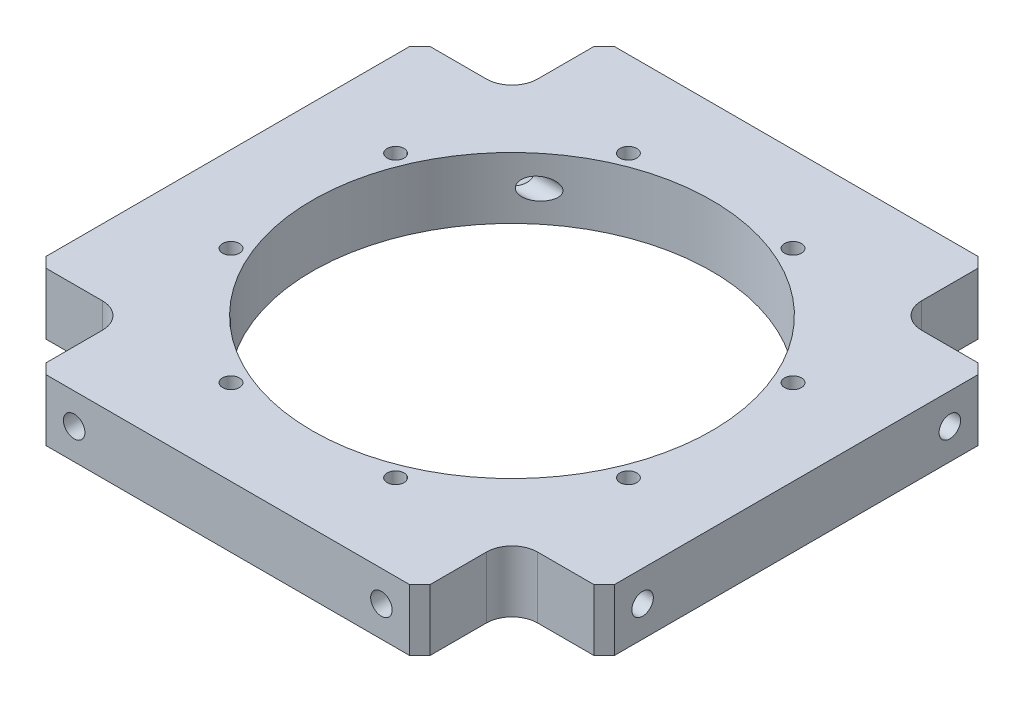
SolidWorks part; units mm, degrees
material "6061-T6 (SS)"
ref_plane "前视基准面" through (0, 0, 0) normal (0, 0, 1) x (1, 0, 0)
ref_plane "上视基准面" through (0, 0, 0) normal (0, 1, 0) x (1, 0, 0)
ref_plane "右视基准面" through (0, 0, 0) normal (1, 0, 0) x (0, 0, -1)
sketch "草图1" plane through (0, 0, 0) normal (0, 1, 0) x (1, 0, 0)
  line L1 (55.5, -55.5) -> (-55.5, -55.5)
  line L2 (55.5, -55.5) -> (55.5, 55.5)
  line L3 (55.5, 55.5) -> (-55.5, 55.5)
  line L4 (-55.5, -55.5) -> (-55.5, 55.5)
  line L5 (55.5, -55.5) -> (-55.5, 55.5) construction
  line L6 (55.5, 55.5) -> (-55.5, -55.5) construction
  point P0 (0, 0)
  dimension "D1" = 111
extrude "凸台-拉伸1" add sketch "草图1" along normal blind 12
sketch "草图2" plane through (0, 12, 0) normal (0, 1, 0) x (1, 0, 0)
  circle A0 centre (0, 0) radius 39
  dimension "D1" = 78
extrude "切除-拉伸1" cut sketch "草图2" against normal through all
sketch "草图4" plane through (0, 12, 0) normal (0, 1, 0) x (1, 0, 0)
  line L0 (0, 55.5) -> (0, 0) construction
  line L1 (55.5, 55.5) -> (-55.5, 55.5) construction
  line L2 (-16.0727, 38.8029) -> (0, 0) construction
  point P0 (-16.0727, 38.8029)
  dimension "D1" = 22.5
  dimension "D2" = 42
hole_wizard "M4 螺纹孔1" positions "草图6" profile "草图7" tap size "M4" standard "GB" end condition through all
sketch "草图6" plane through (0, 12, 0) normal (0, 1, 0) x (1, 0, 0)
  point P0 (-16.0727, 38.8029)
cosmetic thread "孔螺蚊线1" parameters "D2"=4
sketch "草图7" plane through (-16.0727, 12, -38.8029) normal (1, 0, 0) x (0, 0, 1)
  line L0 (0, 0) -> (0, 12)
  line L1 (0, 12) -> (1.65, 12)
  line L2 (1.65, 12) -> (1.65, 0)
  line L5 (1.65, 0) -> (0, 0)
  line L11 (0, -6.35) -> (0, 107.95) construction
  dimension "通孔螺纹孔钻头直径" = 3.3
  dimension "通孔螺纹孔钻头深度" = 12
pattern_circular "阵列(圆周)1" count 8 over 360 about axis through (0, 0, 0) along (0, 1, 0) of "M4 螺纹孔1"
cosmetic thread "孔螺蚊线2" parameters "D2"=4
cosmetic thread "孔螺蚊线3" parameters "D2"=4
cosmetic thread "孔螺蚊线4" parameters "D2"=4
cosmetic thread "孔螺蚊线5" parameters "D2"=4
cosmetic thread "孔螺蚊线6" parameters "D2"=4
cosmetic thread "孔螺蚊线7" parameters "D2"=4
cosmetic thread "孔螺蚊线8" parameters "D2"=4
sketch "草图8" plane through (0, 12, 0) normal (0, 1, 0) x (1, 0, 0)
  line L0 (0, 55.5) -> (0, -55.5) construction
  line L1 (-73.5, 73.5) -> (-37.5, 73.5)
  line L2 (-73.5, 73.5) -> (-73.5, 37.5)
  line L3 (-73.5, 37.5) -> (-37.5, 37.5)
  line L4 (-37.5, 73.5) -> (-37.5, 37.5)
  line L5 (-73.5, 73.5) -> (-37.5, 37.5) construction
  line L6 (-73.5, 37.5) -> (-37.5, 73.5) construction
  line L7 (55.5, 55.5) -> (-55.5, 55.5) construction
  line L8 (-55.5, -55.5) -> (55.5, -55.5) construction
  line L9 (-55.5, 0) -> (55.5, 0) construction
  line L10 (-55.5, 55.5) -> (-55.5, -55.5) construction
  line L11 (55.5, -55.5) -> (55.5, 55.5) construction
  line L12 (73.5, 37.5) -> (37.5, 37.5)
  line L13 (37.5, 73.5) -> (37.5, 37.5)
  line L14 (73.5, 73.5) -> (37.5, 73.5)
  line L15 (73.5, 73.5) -> (73.5, 37.5)
  line L16 (-73.5, -37.5) -> (-37.5, -73.5) construction
  line L17 (-73.5, -73.5) -> (-37.5, -37.5) construction
  line L18 (73.5, -73.5) -> (73.5, -37.5)
  line L19 (73.5, -73.5) -> (37.5, -73.5)
  line L20 (37.5, -73.5) -> (37.5, -37.5)
  line L21 (73.5, -37.5) -> (37.5, -37.5)
  line L22 (-37.5, -73.5) -> (-37.5, -37.5)
  line L23 (-73.5, -37.5) -> (-37.5, -37.5)
  line L24 (-73.5, -73.5) -> (-73.5, -37.5)
  line L25 (-73.5, -73.5) -> (-37.5, -73.5)
  point P0 (-55.5, 55.5)
  point P30 (-55.5, -55.5)
  dimension "D1" = 36
extrude "切除-拉伸2" cut sketch "草图8" against normal through all
fillet "圆角1" radius 5 4 edges at (-37.5, 6, -37.5) (37.5, 6, -37.5) (37.5, 6, 37.5) (-37.5, 6, 37.5)
chamfer "倒角1" distance 2 angle 45 8 edges at (-55.5, 6, -37.5) (-37.5, 6, -55.5) (37.5, 6, -55.5) (55.5, 6, -37.5) (55.5, 6, 37.5) (37.5, 6, 55.5) (-55.5, 6, 37.5) (-37.5, 6, 55.5)
sketch "草图9" plane through (-55.5, 0, 0) normal (-1, 0, 0) x (0, 0, 1)
  line L0 (0, 0) -> (0, 12) construction
  line L1 (-35.5, 0) -> (35.5, 0) construction
  line L2 (-35.5, 12) -> (35.5, 12) construction
  line L3 (-35.5, 6) -> (0, 6) construction
  line L4 (-35.5, 12) -> (-35.5, 0) construction
  point P6 (-30, 6)
  point P12 (30, 6)
  dimension "D1" = 30
hole_wizard "M5 螺纹孔1" positions "草图10" profile "草图11" tap size "M5" standard "GB"
sketch "草图10" plane through (-55.5, 0, 0) normal (-1, 0, 0) x (0, 0, 1)
  point P0 (-30, 6)
  point P3 (30, 6)
sketch "草图11" plane through (-55.5, 6, -30) normal (0, 1, 0) x (0, 0, 1)
  line L0 (0, 0) -> (0, 83.4)
  line L1 (0, 83.4) -> (2.1, 83.4)
  line L2 (2.1, 83.4) -> (2.1, 0)
  line L5 (2.1, 0) -> (0, 0)
  line L11 (0, -6.35) -> (0, 107.95) construction
  dimension "通孔螺纹孔钻头直径" = 4.2
  dimension "通孔螺纹孔钻头深度" = 83.4
cosmetic thread "孔螺蚊线9" parameters "D2"=5
cosmetic thread "孔螺蚊线10" parameters "D2"=5
sketch "草图12" plane through (0, 0, -55.5) normal (0, 0, -1) x (-1, 0, 0)
  line L0 (-35.5, 6) -> (35.5, 6) construction
  line L1 (-35.5, 12) -> (-35.5, 0) construction
  line L2 (35.5, 0) -> (35.5, 12) construction
  line L3 (0, 0) -> (0, 12) construction
  line L4 (-35.5, 0) -> (35.5, 0) construction
  line L5 (-35.5, 12) -> (35.5, 12) construction
  point P12 (-30, 6)
  point P14 (30, 6)
  dimension "D1" = 30
hole_wizard "M5 螺纹孔2" positions "草图15" profile "草图14" tap size "M5" standard "GB"
sketch "草图15" plane through (0, 0, -55.5) normal (0, 0, -1) x (-1, 0, 0)
  point P0 (-30, 6)
  point P3 (30, 6)
sketch "草图14" plane through (30, 6, -55.5) normal (1, 0, 0) x (0, 1, 0)
  line L0 (0, 0) -> (0, 111)
  line L1 (0, 111) -> (2.1, 111)
  line L2 (2.1, 111) -> (2.1, 0)
  line L5 (2.1, 0) -> (0, 0)
  line L11 (0, -6.35) -> (0, 107.95) construction
  dimension "通孔螺纹孔钻头直径" = 4.2
  dimension "通孔螺纹孔钻头深度" = 111
cosmetic thread "孔螺蚊线11" parameters "D2"=5
cosmetic thread "孔螺蚊线12" parameters "D2"=5
mirror "镜向1" about plane through (0, 0, 0) normal (0, 0, 1) of "M5 螺纹孔2"
cosmetic thread "孔螺蚊线13" parameters "D2"=5
cosmetic thread "孔螺蚊线14" parameters "D2"=5
mirror "镜向2" about plane through (0, 0, 0) normal (1, 0, 0) of "M5 螺纹孔1"
cosmetic thread "孔螺蚊线15"
cosmetic thread "孔螺蚊线16"
